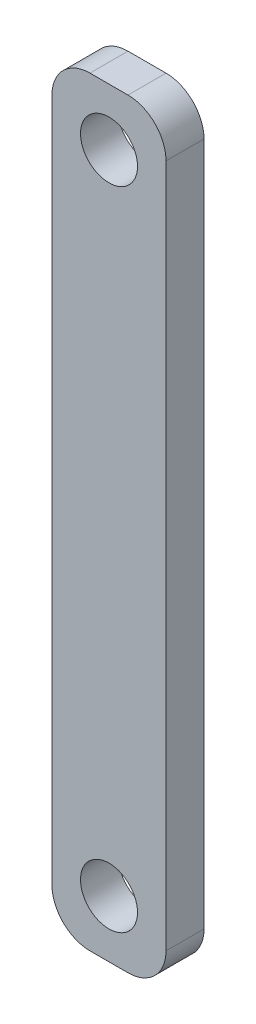
SolidWorks part; units mm, degrees
material "ABS"
ref_plane "Plan de face" through (0, 0, 0) normal (0, 0, 1) x (1, 0, 0)
ref_plane "Plan de dessus" through (0, 0, 0) normal (0, 1, 0) x (1, 0, 0)
ref_plane "Plan de droite" through (0, 0, 0) normal (1, 0, 0) x (0, 0, -1)
sketch "Esquisse2" plane through (0, 0, 0) normal (0, 0, 1) x (1, 0, 0)
  line L0 (0, 0) -> (0, 4.9658) construction
  line L1 (-3, -20) -> (3, -20)
  line L2 (-3, -20) -> (-3, 20)
  line L3 (-3, 20) -> (3, 20)
  line L4 (3, -20) -> (3, 20)
  line L5 (-3, -20) -> (3, 20) construction
  line L6 (-3, 20) -> (3, -20) construction
  circle A0 centre (0, 17) radius 1.5
  circle A1 centre (0, -17) radius 1.5
  point P0 (0, 0)
  dimension "D3" = 3
  dimension "D4" = 0
  dimension "D5" = 3
  dimension "D6" = 3
  dimension "D7" = 3
  dimension "D1" = 34
  dimension "D2" = 6
extrude "Boss.-Extru.2" add sketch "Esquisse2" along normal blind 2
fillet "Congé2" radius 2 4 edges at (-3, 20, 1) (3, 20, 1) (-3, -20, 1) (3, -20, 1)
